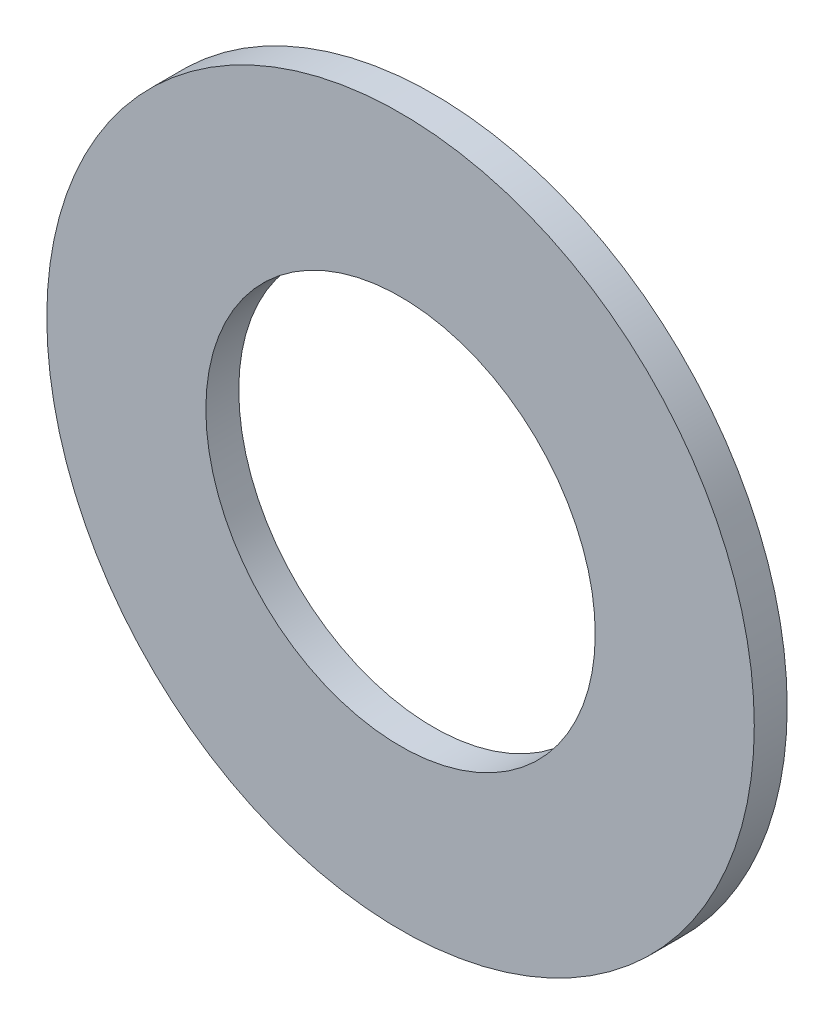
SolidWorks part; units mm, degrees
material "Acrylic (Medium-high impact)"
ref_plane "Front Plane" through (0, 0, 0) normal (0, 0, 1) x (1, 0, 0)
ref_plane "Top Plane" through (0, 0, 0) normal (0, 1, 0) x (1, 0, 0)
ref_plane "Right Plane" through (0, 0, 0) normal (1, 0, 0) x (0, 0, -1)
sketch "Sketch2" plane through (0, 0, 0) normal (0, 0, 1) x (1, 0, 0)
  circle A0 centre (0, 0) radius 32.25
  dimension "D1" = 64.5
extrude "Boss-Extrude1" add sketch "Sketch2" along normal blind 3
sketch "Sketch3" plane through (0, 0, 0) normal (0, 0, -1) x (-1, 0, 0)
  circle A0 centre (0, 0) radius 17.75
  dimension "D1" = 35.5
extrude "Cut-Extrude1" cut sketch "Sketch3" against normal blind 3 contours A0
